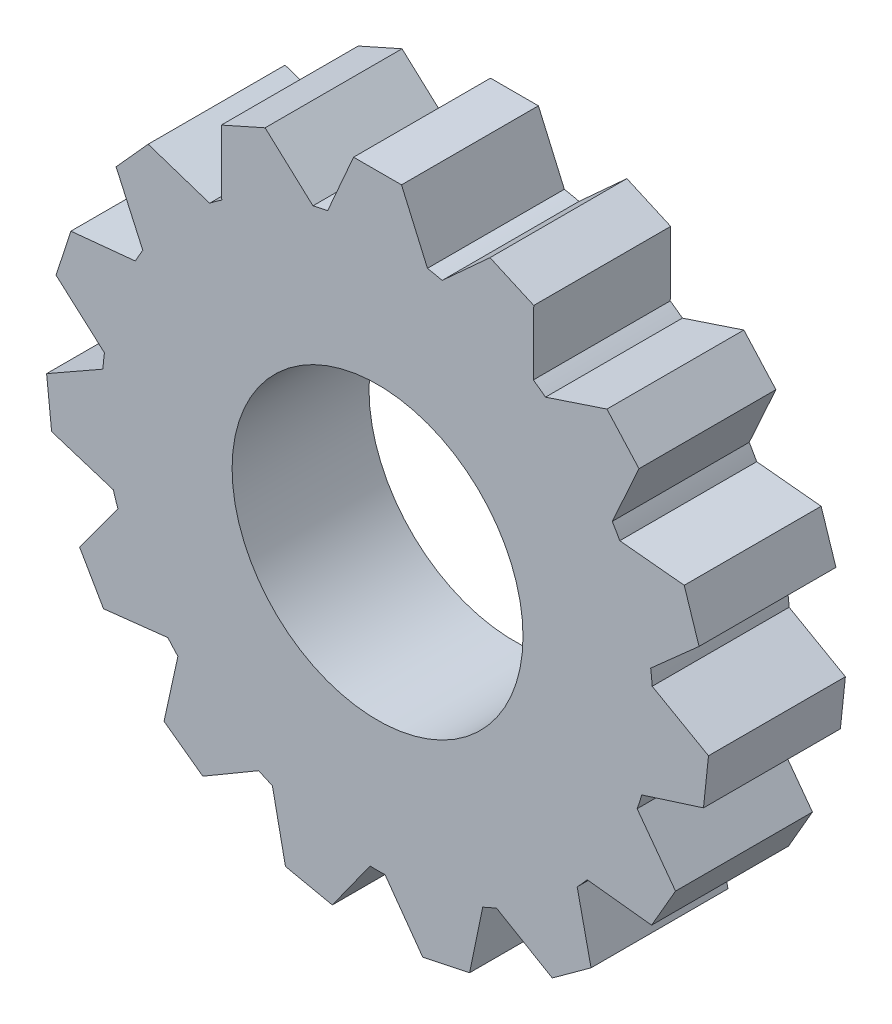
SolidWorks part; units mm, degrees
ref_plane "Front Plane" through (0, 0, 0) normal (0, 0, 1) x (1, 0, 0)
ref_plane "Top Plane" through (0, 0, 0) normal (0, 1, 0) x (1, 0, 0)
ref_plane "Right Plane" through (0, 0, 0) normal (1, 0, 0) x (0, 0, -1)
sketch "Sketch1" plane through (0, 0, 0) normal (0, 0, 1) x (1, 0, 0)
  line L140 (14.5827, 79.1602) -> (7, 96.4922)
  line L141 (7, 96.4922) -> (-7, 96.4922)
  line L142 (-7, 96.4922) -> (-14.5827, 79.1602)
  line L143 (45.5193, 66.3851) -> (45.6417, 85.3028)
  line L144 (45.6417, 85.3028) -> (32.8521, 90.9971)
  line L145 (32.8521, 90.9971) -> (18.8753, 78.2478)
  line L146 (68.5852, 42.1314) -> (76.3916, 59.3638)
  line L147 (76.3916, 59.3638) -> (67.0237, 69.7679)
  line L148 (67.0237, 69.7679) -> (49.0697, 63.8056)
  line L149 (79.7921, 10.5928) -> (93.9326, 23.1603)
  line L150 (93.9326, 23.1603) -> (89.6064, 36.4751)
  line L151 (89.6064, 36.4751) -> (70.7795, 38.3309)
  line L152 (77.2022, -22.7774) -> (95.2319, -17.0478)
  line L153 (95.2319, -17.0478) -> (96.6953, -3.1245)
  line L154 (96.6953, -3.1245) -> (80.2508, 6.2284)
  line L155 (61.2633, -52.2091) -> (80.0647, -54.3083)
  line L156 (80.0647, -54.3083) -> (87.0647, -42.1839)
  line L157 (87.0647, -42.1839) -> (75.8461, -26.9511)
  line L158 (34.7315, -72.6134) -> (51.0536, -82.1783)
  line L159 (51.0536, -82.1783) -> (62.3798, -73.9493)
  line L160 (62.3798, -73.9493) -> (58.3269, -55.4704)
  line L161 (2.1942, -80.4623) -> (13.2148, -95.839)
  line L162 (13.2148, -95.839) -> (26.9089, -92.9282)
  line L163 (26.9089, -92.9282) -> (30.7224, -74.3984)
  line L164 (-30.7224, -74.3984) -> (-26.9089, -92.9282)
  line L165 (-26.9089, -92.9282) -> (-13.2148, -95.839)
  line L166 (-13.2148, -95.839) -> (-2.1942, -80.4623)
  line L167 (-58.3269, -55.4704) -> (-62.3798, -73.9493)
  line L168 (-62.3798, -73.9493) -> (-51.0536, -82.1783)
  line L169 (-51.0536, -82.1783) -> (-34.7315, -72.6134)
  line L170 (-75.8461, -26.9511) -> (-87.0647, -42.1839)
  line L171 (-87.0647, -42.1839) -> (-80.0647, -54.3083)
  line L172 (-80.0647, -54.3083) -> (-61.2633, -52.2091)
  line L173 (-80.2508, 6.2284) -> (-96.6953, -3.1245)
  line L174 (-96.6953, -3.1245) -> (-95.2319, -17.0478)
  line L175 (-95.2319, -17.0478) -> (-77.2022, -22.7774)
  line L176 (-70.7795, 38.3309) -> (-89.6064, 36.4751)
  line L177 (-89.6064, 36.4751) -> (-93.9326, 23.1603)
  line L178 (-93.9326, 23.1603) -> (-79.7921, 10.5928)
  line L179 (-49.0697, 63.8056) -> (-67.0237, 69.7679)
  line L180 (-67.0237, 69.7679) -> (-76.3916, 59.3638)
  line L181 (-76.3916, 59.3638) -> (-68.5852, 42.1314)
  line L182 (-18.8753, 78.2478) -> (-32.8521, 90.9971)
  line L183 (-32.8521, 90.9971) -> (-45.6417, 85.3028)
  line L184 (-45.6417, 85.3028) -> (-45.5193, 66.3851)
  circle A19 centre (0, 0) radius 42.5
  arc A45 (-14.5827, 79.1602) -> (-18.8753, 78.2478) centre (0, 0) ccw
  arc A46 (-45.5193, 66.3851) -> (-49.0697, 63.8056) centre (0, 0) ccw
  arc A47 (18.8753, 78.2478) -> (14.5827, 79.1602) centre (0, 0) ccw
  arc A48 (49.0697, 63.8056) -> (45.5193, 66.3851) centre (0, 0) ccw
  arc A49 (-68.5852, 42.1314) -> (-70.7795, 38.3309) centre (0, 0) ccw
  arc A50 (-79.7921, 10.5928) -> (-80.2508, 6.2284) centre (0, 0) ccw
  arc A51 (-77.2022, -22.7774) -> (-75.8461, -26.9511) centre (0, 0) ccw
  arc A52 (-61.2633, -52.2091) -> (-58.3269, -55.4704) centre (0, 0) ccw
  arc A53 (-34.7315, -72.6134) -> (-30.7224, -74.3984) centre (0, 0) ccw
  arc A54 (-2.1942, -80.4623) -> (2.1942, -80.4623) centre (0, 0) ccw
  arc A55 (30.7224, -74.3984) -> (34.7315, -72.6134) centre (0, 0) ccw
  arc A56 (58.3269, -55.4704) -> (61.2633, -52.2091) centre (0, 0) ccw
  arc A57 (75.8461, -26.9511) -> (77.2022, -22.7774) centre (0, 0) ccw
  arc A58 (80.2508, 6.2284) -> (79.7921, 10.5928) centre (0, 0) ccw
  arc A59 (70.7795, 38.3309) -> (68.5852, 42.1314) centre (0, 0) ccw
  point P66 (0, 0)
  point P109 (0, 0)
  dimension "D1" = 85
extrude "Boss-Extrude3" add sketch "Sketch1" along normal blind 40
